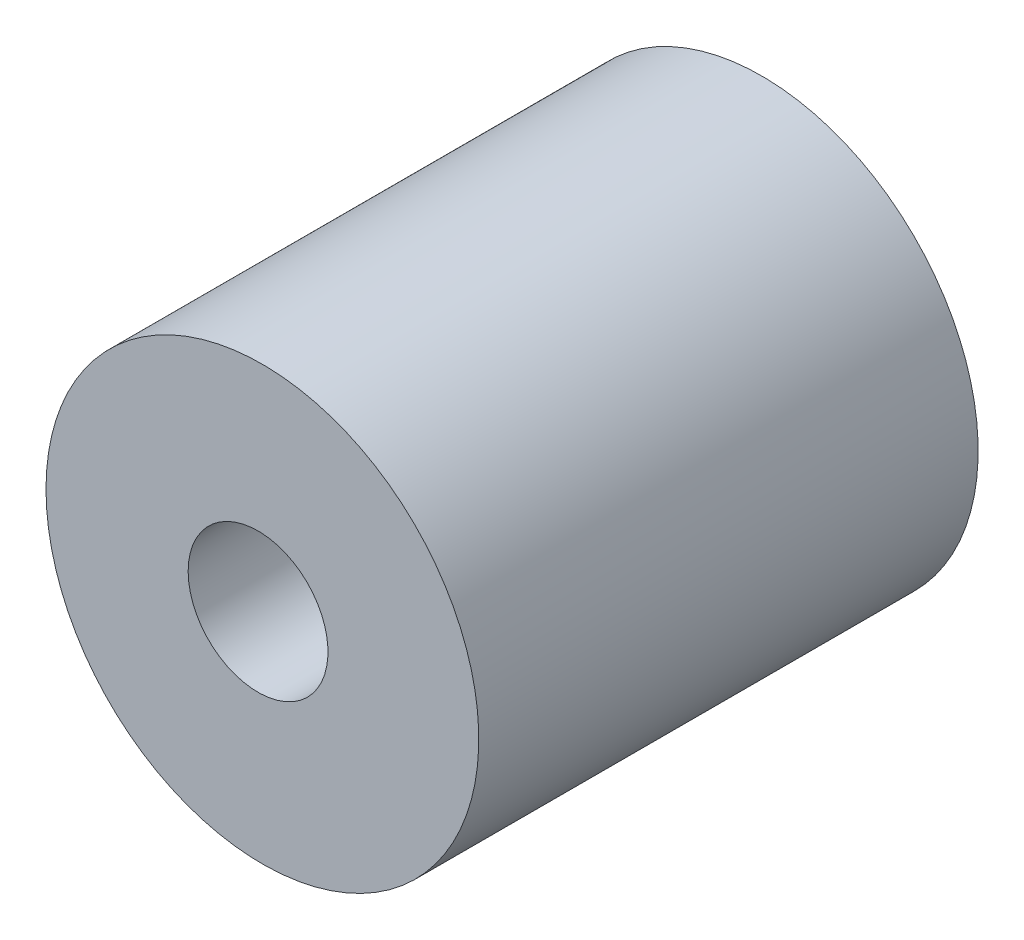
SolidWorks part; units mm, degrees
material "ABS"
ref_plane "Front Plane" through (0, 0, 0) normal (0, 0, 1) x (1, 0, 0)
ref_plane "Top Plane" through (0, 0, 0) normal (0, 1, 0) x (1, 0, 0)
ref_plane "Right Plane" through (0, 0, 0) normal (1, 0, 0) x (0, 0, -1)
sketch "Sketch1" plane through (0, 0, 0) normal (0, 0, 1) x (1, 0, 0)
  circle A0 centre (0, 0) radius 2.667
  circle A1 centre (0.1654, 0) radius 8.255
  dimension "D1" = 5.334
  dimension "D2" = 16.51
extrude "Boss-Extrude1" add sketch "Sketch1" along normal blind 19.05
